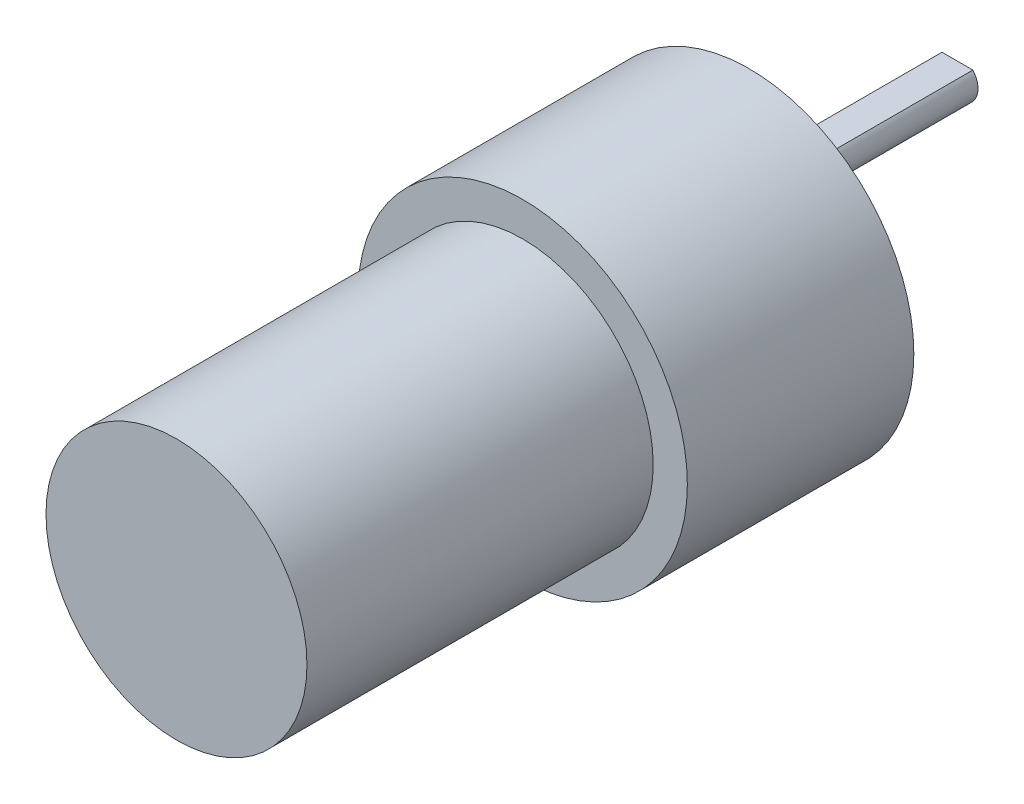
SolidWorks part; units mm, degrees
ref_plane "Front Plane" through (0, 0, 0) normal (0, 0, 1) x (1, 0, 0)
ref_plane "Top Plane" through (0, 0, 0) normal (0, 1, 0) x (1, 0, 0)
ref_plane "Right Plane" through (0, 0, 0) normal (1, 0, 0) x (0, 0, -1)
sketch "Sketch1" plane through (0, 0, 0) normal (0, 1, 0) x (1, 0, 0)
  line L0 (0, 0) -> (0, 32724.5849) construction
  line L1 (0, 0) -> (20.05, 0)
  line L2 (20.05, 0) -> (20.05, 53.2)
  line L3 (20.05, 53.2) -> (25.3, 53.2)
  line L4 (25.3, 53.2) -> (25.3, 88)
  line L5 (25.3, 88) -> (14.25, 88)
  line L6 (14.25, 88) -> (14.25, 89.5)
  line L7 (14.25, 89.5) -> (0, 89.5)
  line L10 (0, 89.5) -> (0, 0)
  point P5 (20.05, 0)
  point P11 (0, 89.5)
  point P12 (0, 90.5967)
  point P17 (3.19, 120)
  point P18 (4.69, 88)
  point P19 (3.19, 87.9026)
  dimension "D1" = 40.1
  dimension "D2" = 50.6
  dimension "D3" = 53.2
  dimension "D4" = 34.8
  dimension "D5" = 1.5
  dimension "D7" = 28.5
revolve "Revolve1" add sketch "Sketch1" angle 360 about L0
sketch "Sketch4" plane through (0, 0, -89.5) normal (0, 0, -1) x (-1, 0, 0)
  circle A0 centre (0, 8.21) radius 3.16
  circle A7 centre (0, 0) radius 14.25 construction
  point P4 (0, 0)
  dimension "D1" = 9.2
  dimension "D2" = 6.32
  dimension "D3" = 8.21
extrude "Boss-Extrude1" add sketch "Sketch4" along normal blind 30.5 contours A0
sketch "Sketch5" plane through (0, 0, -120) normal (0, 0, -1) x (-1, 0, 0)
  line L0 (-2.3701, 10.3) -> (2.3701, 10.3)
  circle A1 centre (0, 8.21) radius 3.16 construction
  circle A2 centre (0, 8.21) radius 3.16 construction
  arc A4 (-2.3701, 10.3) -> (2.3701, 10.3) centre (0, 8.21) cw
  dimension "D1" = 5.25
extrude "Cut-Extrude2" cut sketch "Sketch5" against normal offset from surface (29 mm away) 1.5 up to face at (-3.16, 8.21, -89.5)
sketch "Sketch6" plane through (0, 0, -88) normal (0, 0, -1) x (-1, 0, 0)
  line L2 (0, 0) -> (0, 50000) construction
  circle A2 centre (-19, 0) radius 2.375
  circle A3 centre (19, 0) radius 2.375
  point P0 (-19, 0)
  point P11 (19, 0)
  dimension "D2" = 4.75
  dimension "D3" = 4.75
  dimension "D1" = 38
extrude "Cut-Extrude3" cut sketch "Sketch6" against normal blind 5
